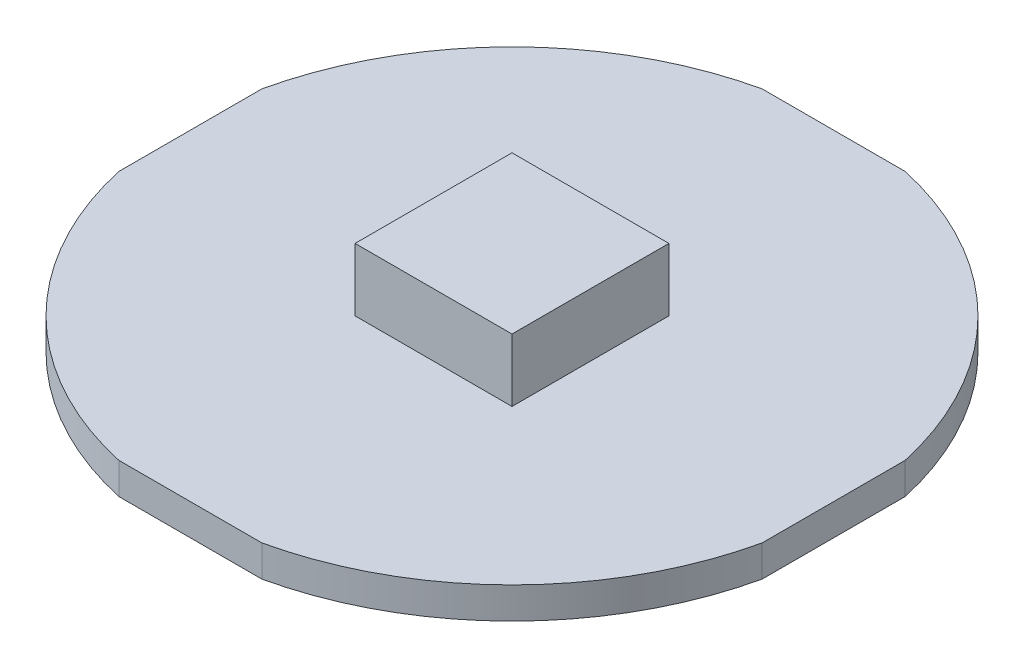
SolidWorks part; units mm, degrees
ref_plane "Front Plane" through (0, 0, 0) normal (0, 0, 1) x (1, 0, 0)
ref_plane "Top Plane" through (0, 0, 0) normal (0, 1, 0) x (1, 0, 0)
ref_plane "Right Plane" through (0, 0, 0) normal (1, 0, 0) x (0, 0, -1)
sketch "Sketch1" plane through (0, 0, 0) normal (0, 1, 0) x (1, 0, 0)
  circle A0 centre (0, 0) radius 16.6688
  dimension "D1" = 33.3375
extrude "Boss-Extrude1" add sketch "Sketch1" along normal blind 1.5875
sketch "Sketch2" plane through (0, 1.5875, 0) normal (0, 1, 0) x (1, 0, 0)
  line L0 (-16.2719, 3.6157) -> (-16.2719, -3.6157)
  line L1 (0, 0) -> (0, -21.9707) construction
  line L2 (0, -0.8731) -> (0, 0.8731) construction
  line L3 (16.2719, 3.6157) -> (16.2719, -3.6157)
  line L4 (0, 0) -> (11.7866, 11.7866) construction
  line L5 (-0.8731, 0) -> (0.8731, 0) construction
  line L6 (3.6157, 16.2719) -> (-3.6157, 16.2719)
  line L7 (3.6157, -16.2719) -> (-3.6157, -16.2719)
  circle A0 centre (0, 0) radius 16.6688 construction
  arc A1 (-16.2719, 3.6157) -> (-16.2719, -3.6157) centre (0, 0) ccw
  arc A2 (16.2719, 3.6157) -> (16.2719, -3.6157) centre (0, 0) cw
  arc A3 (3.6157, 16.2719) -> (-3.6157, 16.2719) centre (0, 0) ccw
  arc A4 (3.6157, -16.2719) -> (-3.6157, -16.2719) centre (0, 0) cw
  dimension "D1" = 45
  dimension "D2" = 0.3969
extrude "Cut-Extrude1" cut sketch "Sketch2" against normal up to next
sketch "Sketch3" plane through (0, 1.5875, 0) normal (0, 1, 0) x (1, 0, 0)
  line L1 (-3.9688, -3.9688) -> (3.9688, -3.9688)
  line L2 (-3.9688, -3.9688) -> (-3.9688, 3.9688)
  line L3 (-3.9688, 3.9688) -> (3.9688, 3.9688)
  line L4 (3.9688, -3.9688) -> (3.9688, 3.9688)
  line L5 (-3.9688, -3.9688) -> (3.9688, 3.9688) construction
  line L6 (-3.9688, 3.9688) -> (3.9688, -3.9688) construction
  point P0 (0, 0)
  dimension "D1" = 7.9375
  dimension "D2" = 7.9375
extrude "Boss-Extrude2" add sketch "Sketch3" along normal blind 3.175 separate body
